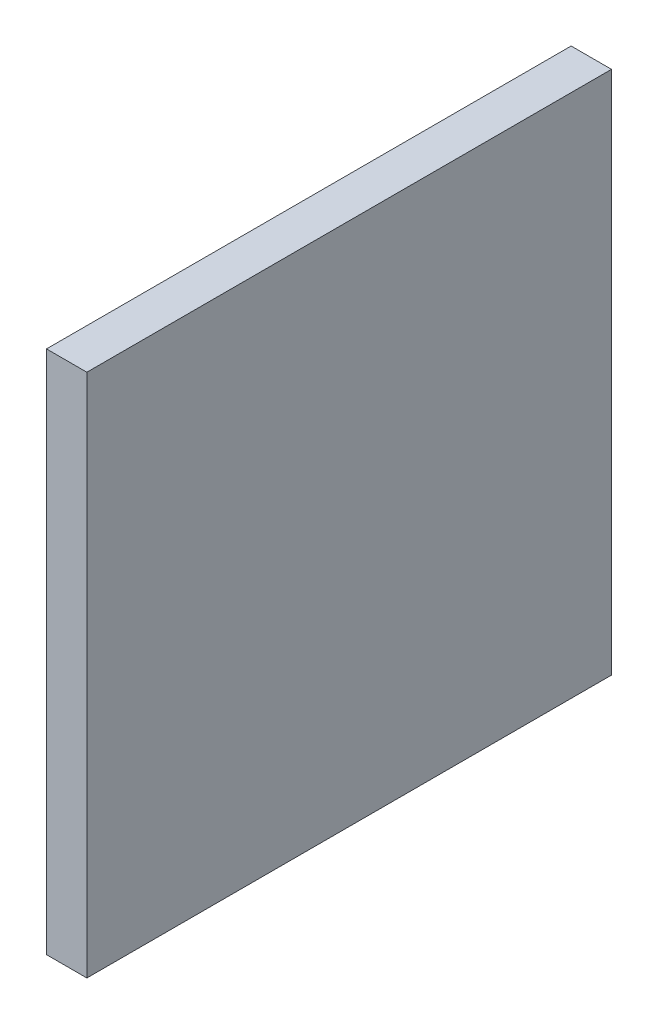
SolidWorks part; units mm, degrees
material "Aleación 1060"
ref_plane "Alzado" through (0, 0, 0) normal (0, 0, 1) x (1, 0, 0)
ref_plane "Planta" through (0, 0, 0) normal (0, 1, 0) x (1, 0, 0)
ref_plane "Vista lateral" through (0, 0, 0) normal (1, 0, 0) x (0, 0, -1)
sketch "Croquis1" plane through (0, 0, 0) normal (1, 0, 0) x (0, 0, -1)
  line L1 (82.5, -82.5) -> (-82.5, -82.5)
  line L2 (82.5, -82.5) -> (82.5, 82.5)
  line L3 (82.5, 82.5) -> (-82.5, 82.5)
  line L4 (-82.5, -82.5) -> (-82.5, 82.5)
  line L5 (82.5, -82.5) -> (-82.5, 82.5) construction
  line L6 (82.5, 82.5) -> (-82.5, -82.5) construction
  point P0 (0, 0)
  dimension "D1" = 165
  dimension "D2" = 165
extrude "Saliente-Extruir1" add sketch "Croquis1" along normal blind 12.7
